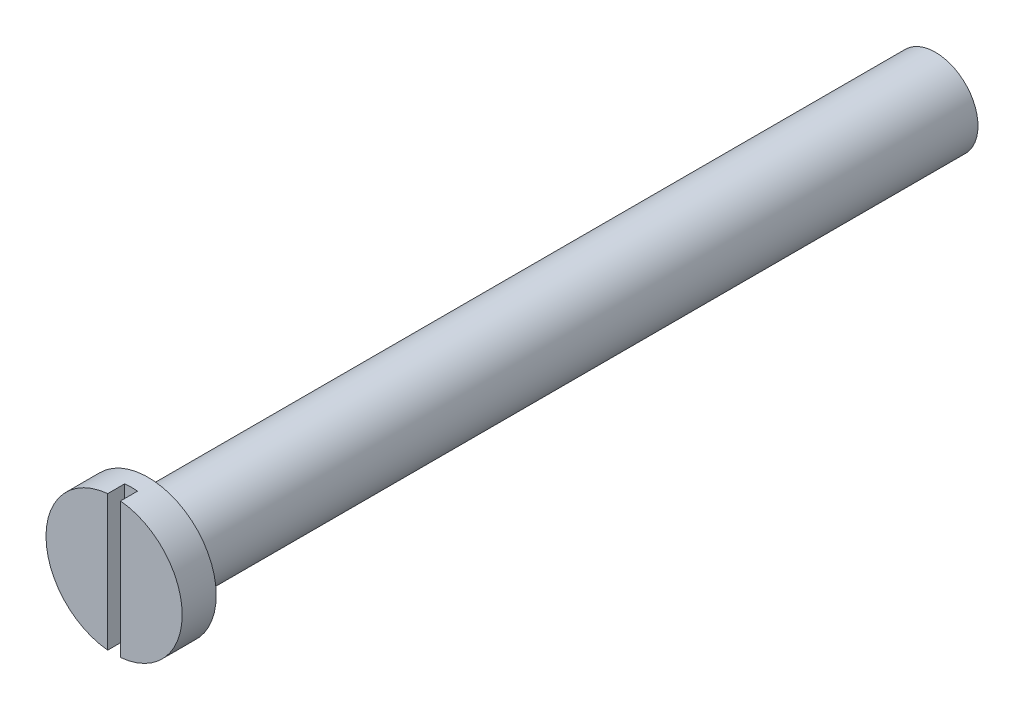
SolidWorks part; units mm, degrees
ref_plane "前视基准面" through (0, 0, 0) normal (0, 0, 1) x (1, 0, 0)
ref_plane "上视基准面" through (0, 0, 0) normal (0, 1, 0) x (1, 0, 0)
ref_plane "右视基准面" through (0, 0, 0) normal (1, 0, 0) x (0, 0, -1)
sketch "草图1" plane through (0, 0, 0) normal (0, 0, 1) x (1, 0, 0)
  circle A0 centre (0, 0) radius 5
  dimension "D1" = 10
extrude "凸台-拉伸1" add sketch "草图1" along normal blind 92.5
cosmetic thread "装饰螺纹线2" parameters "D1"=10, "D2"=4.134
sketch "草图2" plane through (0, 0, 92.5) normal (0, 0, 1) x (1, 0, 0)
  circle A0 centre (0, 0) radius 8
  dimension "D1" = 16
extrude "凸台-拉伸2" add sketch "草图2" along normal blind 4
sketch "草图4" plane through (0, 0, 96.5) normal (0, 0, 1) x (1, 0, 0)
  line L1 (-0.75, 9.78) -> (0.75, 9.78)
  line L2 (-0.75, 9.78) -> (-0.75, -9.78)
  line L3 (-0.75, -9.78) -> (0.75, -9.78)
  line L4 (0.75, 9.78) -> (0.75, -9.78)
  line L5 (-0.75, 9.78) -> (0.75, -9.78) construction
  line L6 (-0.75, -9.78) -> (0.75, 9.78) construction
  point P0 (0, 0)
  dimension "D1" = 1.5
extrude "切除-拉伸1" cut sketch "草图4" against normal blind 2
sketch "草图5" plane through (0, 0, 0) normal (0, 0, -1) x (-1, 0, 0)
  point P0 (0, 0)
  point P1 (-8.9921, 4.042)
hole_wizard "M8 螺纹孔的螺纹孔钻头1" positions "草图6" profile "草图8" hole size "M8" standard "GB"
sketch "草图6" plane through (0, 0, 0) normal (0, 0, -1) x (-1, 0, 0)
  point P0 (0, 0)
sketch "草图8" plane through (0, 0, 0) normal (1, 0, 0) x (0, 1, 0)
  line L0 (0, 0) -> (0, 17.0429)
  line L1 (0, 17.0429) -> (3.4, 15)
  line L2 (3.4, 15) -> (3.4, 0)
  line L5 (3.4, 0) -> (0, 0)
  line L10 (0, 17.0429) -> (-3.4, 15) construction
  line L11 (0, -6.35) -> (0, 107.95) construction
  dimension "孔直径" = 6.8
  dimension "孔深度" = 15
  dimension "导头角度" = 118
